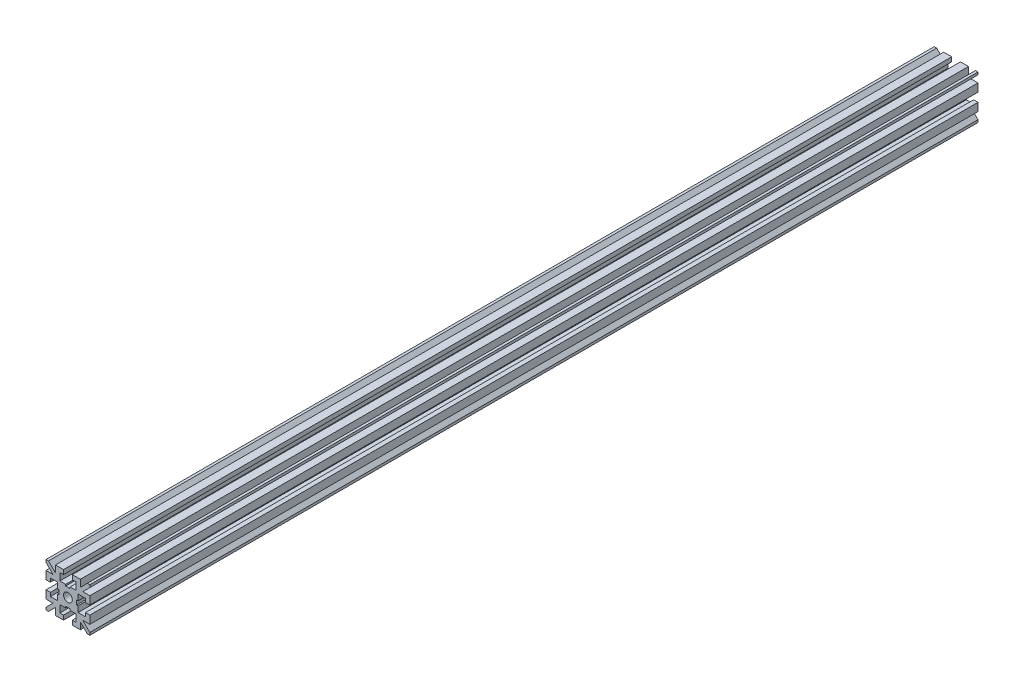
SolidWorks part; units mm, degrees
ref_plane "Front Plane" through (0, 0, 0) normal (0, 0, 1) x (1, 0, 0)
ref_plane "Top Plane" through (0, 0, 0) normal (0, 1, 0) x (1, 0, 0)
ref_plane "Right Plane" through (0, 0, 0) normal (1, 0, 0) x (0, 0, -1)
sketch "Sketch1" plane through (0, 0, 0) normal (0, 0, 1) x (1, 0, 0)
  line L1 (-9.0006, 3.7616) -> (5.9994, 3.7616)
  line L2 (-9.0006, 3.7616) -> (-9.0006, -11.2384)
  line L3 (-9.0006, -11.2384) -> (5.9994, -11.2384)
  line L4 (5.9994, 3.7616) -> (5.9994, -11.2384)
  dimension "D1" = 15
  dimension "D2" = 15
extrude "Boss-Extrude1" add sketch "Sketch1" along normal blind 304.19
sketch "Sketch2" plane through (0, 0, 304.19) normal (0, 0, 1) x (1, 0, 0)
  line L0 (-9.0006, 3.7616) -> (5.9994, -11.2384) construction
  line L1 (5.9994, 3.7616) -> (-9.0006, -11.2384) construction
  line L4 (1.9994, -4.4884) -> (1.9994, -6.4884)
  line L5 (5.9994, -3.7384) -> (1.9994, -3.7384) construction
  line L6 (5.9994, -11.2384) -> (5.9994, 3.7616) construction
  line L7 (-1.5006, 3.7616) -> (-1.5006, -3.7384) construction
  line L8 (5.9994, 3.7616) -> (-9.0006, 3.7616) construction
  line L9 (-9.0006, -3.7384) -> (-1.5006, -3.7384) construction
  line L10 (-9.0006, 3.7616) -> (-9.0006, -11.2384) construction
  line L11 (-1.5006, -11.2384) -> (-1.5006, -3.7384) construction
  line L12 (-9.0006, -11.2384) -> (5.9994, -11.2384) construction
  line L13 (1.9994, -4.4884) -> (1.4994, -4.4884)
  line L14 (1.9994, -0.9884) -> (4.4994, -0.9884)
  line L15 (1.9994, -0.9884) -> (1.9994, -2.9884)
  line L16 (1.9994, -6.4884) -> (4.4994, -6.4884)
  line L17 (4.4994, -0.9884) -> (4.4994, -6.4884)
  line L18 (-4.2506, -7.2384) -> (-4.2506, -9.7384)
  line L19 (1.9994, -2.9884) -> (1.4994, -2.9884)
  line L20 (1.4994, -4.4884) -> (1.4994, -2.9884)
  line L21 (1.4994, -3.7384) -> (-0.0006, -3.7384) construction
  line L22 (-2.2506, -7.2384) -> (-4.2506, -7.2384)
  line L23 (-2.2506, -7.2384) -> (-2.2506, -6.7384)
  line L24 (-2.2506, -6.7384) -> (-0.7506, -6.7384)
  line L25 (-0.7506, -7.2384) -> (-0.7506, -6.7384)
  line L26 (1.2494, -7.2384) -> (-0.7506, -7.2384)
  line L27 (1.2494, -7.2384) -> (1.2494, -9.7384)
  line L28 (1.2494, -9.7384) -> (-4.2506, -9.7384)
  line L29 (-5.0006, -0.9884) -> (-7.5006, -0.9884)
  line L30 (-5.0006, -2.9884) -> (-5.0006, -0.9884)
  line L31 (-5.0006, -2.9884) -> (-4.5006, -2.9884)
  line L32 (-4.5006, -2.9884) -> (-4.5006, -4.4884)
  line L33 (-5.0006, -4.4884) -> (-4.5006, -4.4884)
  line L34 (-5.0006, -6.4884) -> (-5.0006, -4.4884)
  line L35 (-5.0006, -6.4884) -> (-7.5006, -6.4884)
  line L36 (-7.5006, -6.4884) -> (-7.5006, -0.9884)
  line L37 (1.2494, -0.2384) -> (1.2494, 2.2616)
  line L38 (-0.7506, -0.2384) -> (1.2494, -0.2384)
  line L39 (-0.7506, -0.2384) -> (-0.7506, -0.7384)
  line L40 (-0.7506, -0.7384) -> (-2.2506, -0.7384)
  line L41 (-2.2506, -0.2384) -> (-2.2506, -0.7384)
  line L42 (-4.2506, -0.2384) -> (-2.2506, -0.2384)
  line L43 (-4.2506, -0.2384) -> (-4.2506, 2.2616)
  line L44 (-4.2506, 2.2616) -> (1.2494, 2.2616)
  circle A0 centre (-1.5006, -3.7384) radius 1.5
  point P60 (-1.5006, -3.7384)
  dimension "D1" = 5.5
  dimension "D2" = 2.5
  dimension "D3" = 1.5
  dimension "D4" = 2.75
  dimension "D5" = 0.5
  dimension "D6" = 1.5
  dimension "D7" = 0.75
  dimension "D8" = 4
extrude "Cut-Extrude1" cut sketch "Sketch2" against normal up to surface (304.19 mm away) up to face at (-1.5006, -3.7384, 0)
sketch "Sketch3" plane through (0, 0, 304.19) normal (0, 0, 1) x (1, 0, 0)
  line L0 (5.9994, 3.7616) -> (-9.0006, -11.2384) construction
  line L1 (-9.0006, 3.7616) -> (5.9994, -11.2384) construction
  line L2 (5.1509, 3.7616) -> (2.7494, 1.3602)
  line L3 (5.9994, 3.7616) -> (-9.0006, 3.7616) construction
  line L4 (2.7494, 1.3602) -> (2.7494, 3.7616)
  line L5 (2.7494, 3.7616) -> (5.1509, 3.7616)
  line L6 (1.2494, -0.2384) -> (1.2494, 2.2616) construction
  line L7 (5.9994, 0.5116) -> (5.9994, 2.9131)
  line L8 (3.5979, 0.5116) -> (5.9994, 0.5116)
  line L9 (5.9994, 2.9131) -> (3.5979, 0.5116)
  line L10 (1.2494, 2.2616) -> (-4.2506, 2.2616) construction
  line L11 (-3.0006, 3.7616) -> (-0.0006, 3.7616)
  line L12 (-3.0006, 3.7616) -> (-3.0006, 2.2616)
  line L13 (-3.0006, 2.2616) -> (-0.0006, 2.2616)
  line L14 (-0.0006, 3.7616) -> (-0.0006, 2.2616)
  line L15 (-2.2506, -0.7384) -> (-0.7506, -0.7384) construction
  line L16 (2.7494, -8.8369) -> (2.7494, -11.2384)
  line L17 (2.7494, -11.2384) -> (5.1509, -11.2384)
  line L18 (5.1509, -11.2384) -> (2.7494, -8.8369)
  line L19 (5.9994, -10.3898) -> (3.5979, -7.9884)
  line L20 (3.5979, -7.9884) -> (5.9994, -7.9884)
  line L21 (5.9994, -7.9884) -> (5.9994, -10.3898)
  line L22 (5.9994, -5.2384) -> (4.4994, -5.2384)
  line L23 (5.9994, -2.2384) -> (5.9994, -5.2384)
  line L24 (5.9994, -2.2384) -> (4.4994, -2.2384)
  line L25 (4.4994, -2.2384) -> (4.4994, -5.2384)
  line L26 (-6.5991, -7.9884) -> (-9.0006, -7.9884)
  line L27 (-9.0006, -7.9884) -> (-9.0006, -10.3898)
  line L28 (-9.0006, -10.3898) -> (-6.5991, -7.9884)
  line L29 (-8.1521, -11.2384) -> (-5.7506, -8.8369)
  line L30 (-5.7506, -8.8369) -> (-5.7506, -11.2384)
  line L31 (-5.7506, -11.2384) -> (-8.1521, -11.2384)
  line L32 (-3.0006, -11.2384) -> (-3.0006, -9.7384)
  line L33 (-0.0006, -11.2384) -> (-3.0006, -11.2384)
  line L34 (-0.0006, -11.2384) -> (-0.0006, -9.7384)
  line L35 (-0.0006, -9.7384) -> (-3.0006, -9.7384)
  line L36 (-5.7506, 1.3602) -> (-5.7506, 3.7616)
  line L37 (-5.7506, 3.7616) -> (-8.1521, 3.7616)
  line L38 (-8.1521, 3.7616) -> (-5.7506, 1.3602)
  line L39 (-9.0006, 2.9131) -> (-6.5991, 0.5116)
  line L40 (-6.5991, 0.5116) -> (-9.0006, 0.5116)
  line L41 (-9.0006, 0.5116) -> (-9.0006, 2.9131)
  line L42 (-9.0006, -2.2384) -> (-7.5006, -2.2384)
  line L43 (-9.0006, -5.2384) -> (-9.0006, -2.2384)
  line L44 (-9.0006, -5.2384) -> (-7.5006, -5.2384)
  line L45 (-7.5006, -5.2384) -> (-7.5006, -2.2384)
  point P24 (-1.5006, -0.7384)
  point P27 (-1.5006, -3.7384)
  point P61 (-1.5006, -3.7384)
  dimension "D1" = 0.6
  dimension "D2" = 1.5
  dimension "D3" = 3
  dimension "D4" = 1.5
  dimension "D5" = 4
extrude "Cut-Extrude2" cut sketch "Sketch3" against normal up to surface (304.19 mm away) up to face at (-1.5006, 0.2616, 0)
